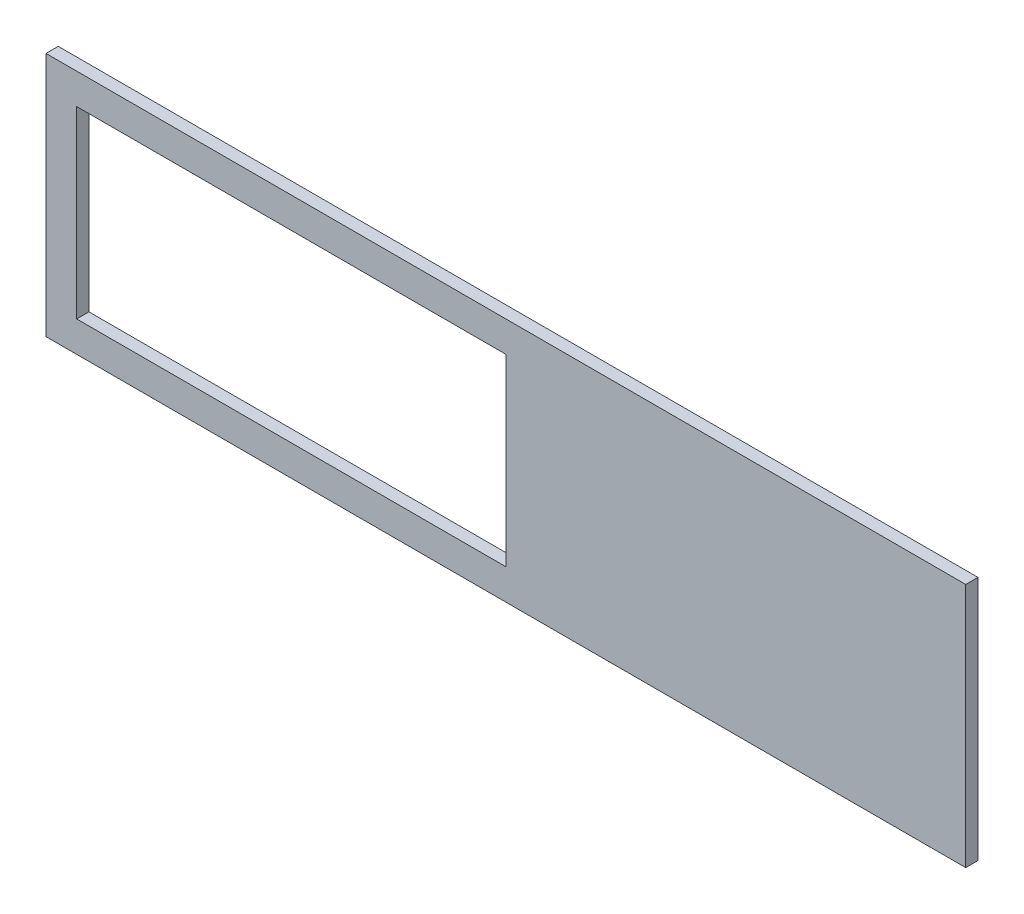
SolidWorks part; units mm, degrees
ref_plane "Alzado" through (0, 0, 0) normal (0, 0, 1) x (1, 0, 0)
ref_plane "Planta" through (0, 0, 0) normal (0, 1, 0) x (1, 0, 0)
ref_plane "Vista lateral" through (0, 0, 0) normal (1, 0, 0) x (0, 0, -1)
sketch "Croquis1" plane through (0, 0, 0) normal (0, 0, 1) x (1, 0, 0)
  line L1 (0, 0) -> (300, 0)
  line L2 (0, 0) -> (0, 80)
  line L3 (0, 80) -> (300, 80)
  line L4 (300, 0) -> (300, 80)
  line L5 (10, 70) -> (150, 70)
  line L6 (10, 70) -> (10, 10)
  line L7 (10, 10) -> (150, 10)
  line L8 (150, 70) -> (150, 10)
  dimension "D1" = 80
  dimension "D2" = 300
  dimension "D3" = 10
  dimension "D4" = 10
  dimension "D5" = 10
  dimension "D6" = 140
extrude "Saliente-Extruir1" add sketch "Croquis1" along normal blind 4
